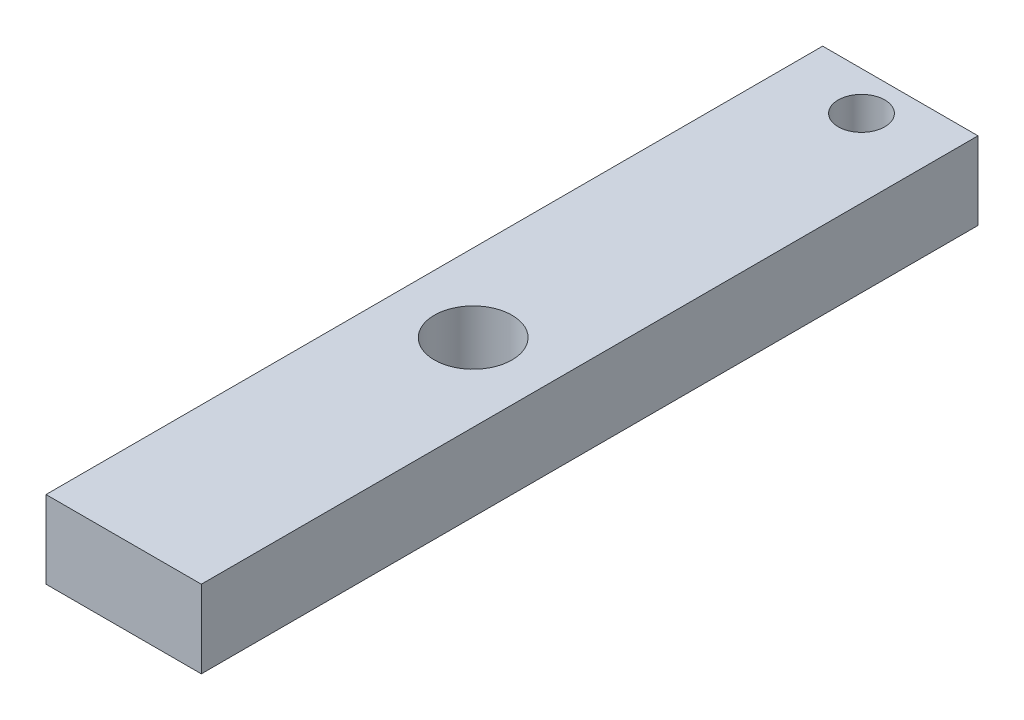
SolidWorks part; units mm, degrees
ref_plane "Front Plane" through (0, 0, 0) normal (0, 0, 1) x (1, 0, 0)
ref_plane "Top Plane" through (0, 0, 0) normal (0, 1, 0) x (1, 0, 0)
ref_plane "Right Plane" through (0, 0, 0) normal (1, 0, 0) x (0, 0, -1)
sketch "Sketch1" plane through (0, 0, 0) normal (0, 1, 0) x (1, 0, 0)
  line L0 (-10, 40) -> (10, 40) construction
  line L1 (-10, -50) -> (10, -50)
  line L2 (-10, -50) -> (-10, 50)
  line L3 (-10, 50) -> (10, 50)
  line L4 (10, -50) -> (10, 50)
  line L5 (-10, -50) -> (10, 50) construction
  line L6 (-10, 50) -> (10, -50) construction
  line L7 (10, 40) -> (-10, -50) construction
  line L8 (10, -50) -> (-10, 40) construction
  circle A1 centre (0, 45) radius 3
  circle A3 centre (0, -5) radius 5
  point P0 (0, 0)
  dimension "D3" = 10
  dimension "D5" = 6
  dimension "D1" = 20
  dimension "D2" = 100
  dimension "D4" = 5
  dimension "D7" = 10
extrude "Boss-Extrude1" add sketch "Sketch1" along normal blind 10
